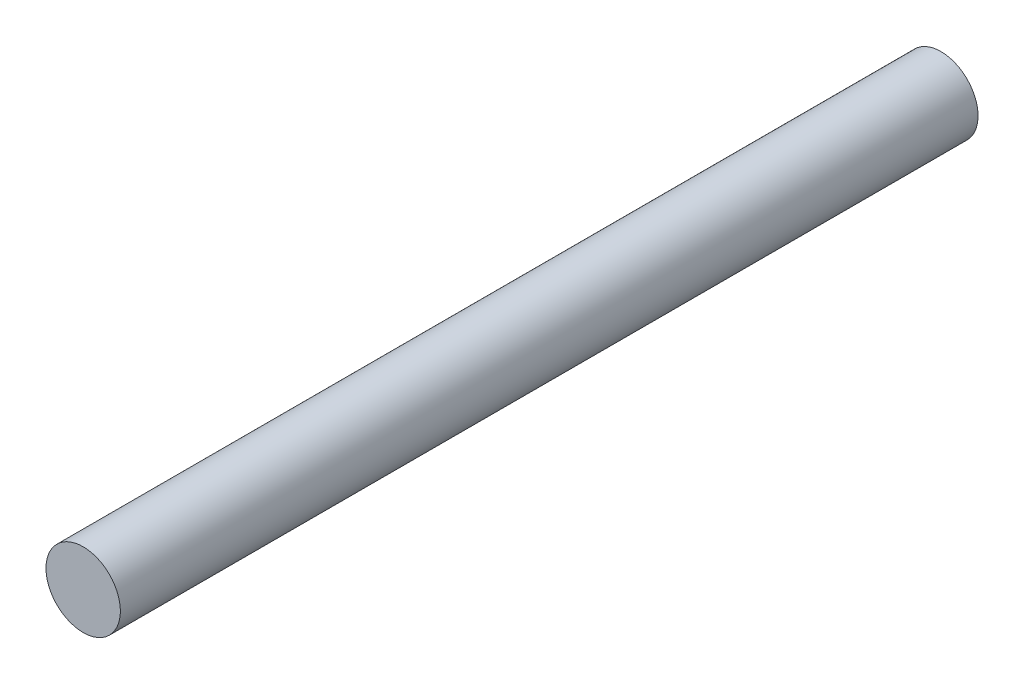
SolidWorks part; units mm, degrees
ref_plane "Front Plane" through (0, 0, 0) normal (0, 0, 1) x (1, 0, 0)
ref_plane "Top Plane" through (0, 0, 0) normal (0, 1, 0) x (1, 0, 0)
ref_plane "Right Plane" through (0, 0, 0) normal (1, 0, 0) x (0, 0, -1)
sketch "Sketch1" plane through (0, 0, 0) normal (0, 0, 1) x (1, 0, 0)
  circle A0 centre (0, 0) radius 3.9
  dimension "D1" = 7.8
extrude "Boss-Extrude1" add sketch "Sketch1" along normal blind 90
